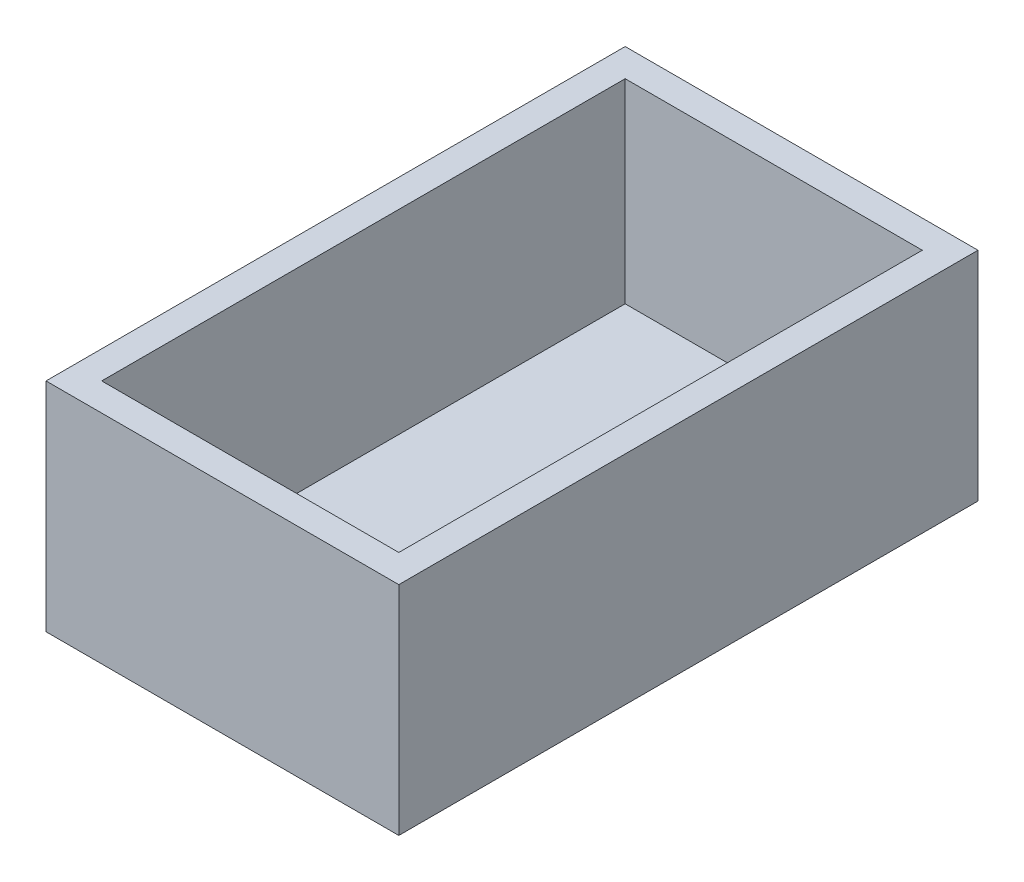
SolidWorks part; units mm, degrees
ref_plane "Piano frontale" through (0, 0, 0) normal (0, 0, 1) x (1, 0, 0)
ref_plane "Piano superiore" through (0, 0, 0) normal (0, 1, 0) x (1, 0, 0)
ref_plane "Piano destro" through (0, 0, 0) normal (1, 0, 0) x (0, 0, -1)
sketch "Schizzo1" plane through (0, 0, 0) normal (0, 1, 0) x (1, 0, 0)
  line L1 (0, 0) -> (63.34, 0)
  line L2 (0, 0) -> (0, 103.98)
  line L3 (0, 103.98) -> (63.34, 103.98)
  line L4 (63.34, 0) -> (63.34, 103.98)
  dimension "D1" = 63.34
  dimension "D2" = 103.98
extrude "Estrusione-Estrusione1" add sketch "Schizzo1" along normal blind 4
sketch "Schizzo2" plane through (0, 4, 0) normal (0, 1, 0) x (1, 0, 0)
  line L0 (5, 98.98) -> (5, 5)
  line L1 (0, 103.98) -> (63.34, 103.98)
  line L2 (0, 103.98) -> (0, 0)
  line L3 (0, 0) -> (63.34, 0)
  line L4 (63.34, 103.98) -> (63.34, 0)
  line L5 (5, 5) -> (58.34, 5)
  line L6 (58.34, 98.98) -> (58.34, 5)
  line L7 (5, 98.98) -> (58.34, 98.98)
  dimension "D1" = 5
extrude "Estrusione-Estrusione2" add sketch "Schizzo2" along normal blind 35
